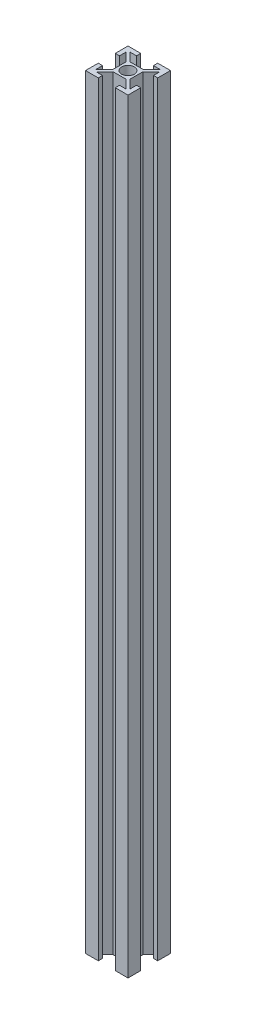
SolidWorks part; units mm, degrees
material "1060 Alloy"
ref_plane "Front Plane" through (0, 0, 0) normal (0, 0, 1) x (1, 0, 0)
ref_plane "Top Plane" through (0, 0, 0) normal (0, 1, 0) x (1, 0, 0)
ref_plane "Right Plane" through (0, 0, 0) normal (1, 0, 0) x (0, 0, -1)
sketch "2020 sketch" plane through (0, 0, 0) normal (0, 1, 0) x (1, 0, 0)
  line L0 (-4, 10) -> (-4, 8)
  line L1 (-10, 10) -> (-4, 10)
  line L2 (-10, 10) -> (-10, 4)
  line L3 (-10, -10) -> (-4, -10)
  line L4 (10, 10) -> (10, 4)
  line L5 (-10, 10) -> (10, -10) construction
  line L6 (-10, -10) -> (10, 10) construction
  line L7 (-4, 8) -> (-7, 8)
  line L8 (-7, 8) -> (-3, 4)
  line L9 (-3, 4) -> (3, 4)
  line L10 (3, 4) -> (7, 8)
  line L11 (7, 8) -> (4, 8)
  line L12 (4, 8) -> (4, 10)
  line L13 (4, 3) -> (4, -3)
  line L14 (8, 7) -> (4, 3)
  line L15 (8, 4) -> (8, 7)
  line L16 (10, 4) -> (8, 4)
  line L17 (8, -4) -> (10, -4)
  line L18 (8, -7) -> (8, -4)
  line L19 (4, -3) -> (8, -7)
  line L20 (3, -4) -> (-3, -4)
  line L21 (7, -8) -> (3, -4)
  line L22 (4, -8) -> (7, -8)
  line L23 (4, -10) -> (4, -8)
  line L24 (-4, -8) -> (-4, -10)
  line L25 (-7, -8) -> (-4, -8)
  line L26 (-3, -4) -> (-7, -8)
  line L27 (-4, -3) -> (-4, 3)
  line L28 (-8, -7) -> (-4, -3)
  line L29 (-8, -4) -> (-8, -7)
  line L30 (-10, -4) -> (-8, -4)
  line L31 (-8, 4) -> (-10, 4)
  line L32 (-8, 7) -> (-8, 4)
  line L33 (-4, 3) -> (-8, 7)
  line L34 (-10, -4) -> (-10, -10)
  line L35 (10, -4) -> (10, -10)
  line L36 (4, 10) -> (10, 10)
  line L37 (4, -10) -> (10, -10)
  circle A0 centre (0, 0) radius 3
  point P0 (0, 0)
  point P14 (4, 9)
  point P42 (0, 0)
  dimension "D9" = 6
  dimension "D1" = 20
  dimension "D2" = 20
  dimension "D3" = 8
  dimension "D4" = 6
  dimension "D5" = 6
  dimension "D6" = 2
  dimension "D7" = 4
  dimension "D8" = 4
extrude "Boss-Extrude1" add sketch "2020 sketch" along normal blind 360 contours A0 | L28 L27 L33 L32 L31 L2 L1 L0 L7 L8 L9 L10 L11 L12 L36 L4 L16 L15 L14 L13 L19 L18 L17 L35 L37 L23 L22 L21 L20 L26 L25 L24 L3 L34 L30 L29
